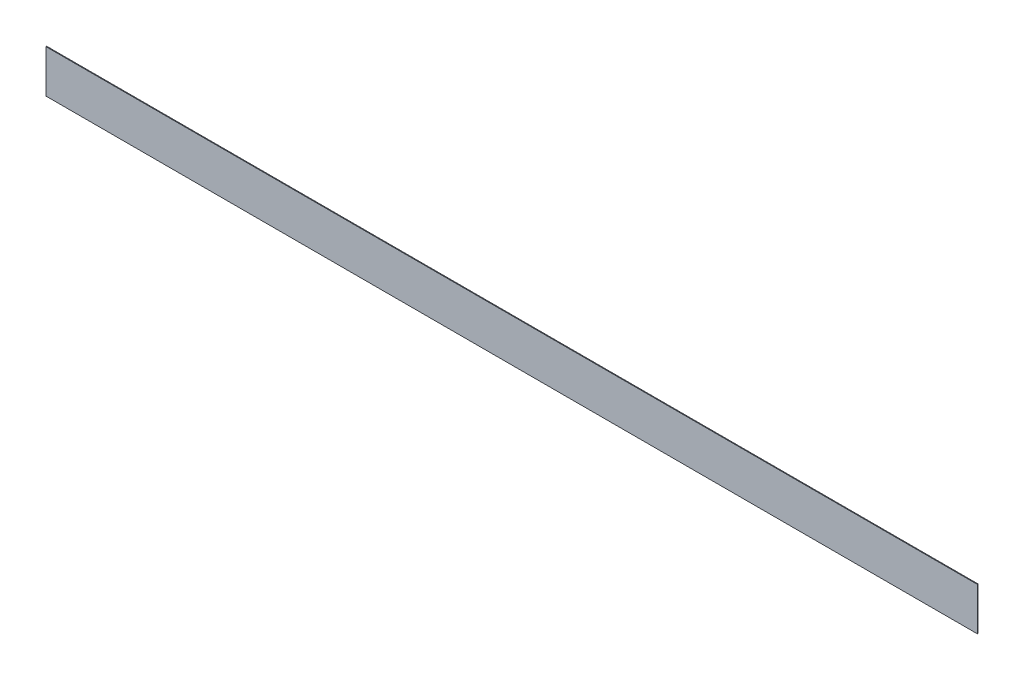
SolidWorks part; units mm, degrees
ref_plane "Front Plane" through (0, 0, 0) normal (0, 0, 1) x (1, 0, 0)
ref_plane "Top Plane" through (0, 0, 0) normal (0, 1, 0) x (1, 0, 0)
ref_plane "Right Plane" through (0, 0, 0) normal (1, 0, 0) x (0, 0, -1)
sketch "Sketch1" plane through (0, 0, 0) normal (0, 0, 1) x (1, 0, 0)
  line L0 (2500, 115) -> (2500, 0)
  line L1 (2500, 115) -> (0, 115)
  line L2 (2500, 0) -> (0, 0)
  line L3 (0, 115) -> (0, 0)
other "Pen Sketch1" parameters "D1"=69.7562, "D2"=44.2015
extrude "Boss-Extrude1" add sketch "Sketch1" along normal blind 2
